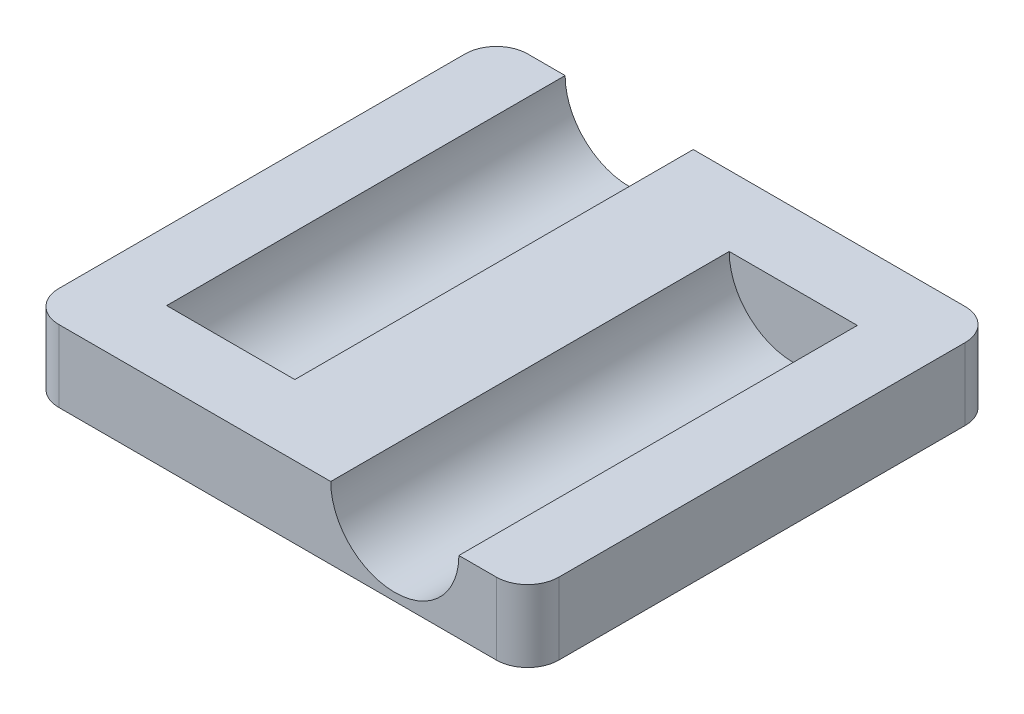
SolidWorks part; units mm, degrees
ref_plane "Front Plane" through (0, 0, 0) normal (0, 0, 1) x (1, 0, 0)
ref_plane "Top Plane" through (0, 0, 0) normal (0, 1, 0) x (1, 0, 0)
ref_plane "Right Plane" through (0, 0, 0) normal (1, 0, 0) x (0, 0, -1)
sketch "Sketch1" plane through (0, 0, 0) normal (0, 0, 1) x (1, 0, 0)
  line L1 (-12.0457, -6.5978) -> (19.9543, -6.5978)
  line L2 (-12.0457, -6.5978) -> (-12.0457, -0.0978)
  line L3 (-12.0457, -0.0978) -> (19.9543, -0.0978)
  line L4 (19.9543, -6.5978) -> (19.9543, -0.0978)
  dimension "D1" = 32
  dimension "D2" = 6.5
extrude "Boss-Extrude1" add sketch "Sketch1" along normal blind 30
fillet "Fillet1" radius 2 4 edges at (19.9543, -3.3478, 30) (-12.0457, -3.3478, 30) (-12.0457, -3.3478, 0) (19.9543, -3.3478, 0)
sketch "Sketch2" plane through (0, 0, 0) normal (0, 0, -1) x (-1, 0, 0)
  circle A0 centre (3.5457, -0.1978) radius 4.1
extrude "Cut-Extrude1" cut sketch "Sketch2" against normal blind 25.5
sketch "Sketch3" plane through (0, 0, 30) normal (0, 0, 1) x (1, 0, 0)
  circle A0 centre (11.4543, -0.1978) radius 4.1
extrude "Cut-Extrude2" cut sketch "Sketch3" against normal blind 25.5
sketch "Sketch5" plane through (0, 0, 30) normal (0, 0, 1) x (1, 0, 0)
  line L0 (19.9543, -0.0978) -> (19.9543, -6.5978) construction
  line L1 (-12.0457, -0.0978) -> (19.9543, -0.0978)
  line L2 (-12.0457, -0.0978) -> (-12.0457, -0.1978)
  line L3 (-12.0457, -0.1978) -> (19.9543, -0.1978)
  line L4 (19.9543, -0.0978) -> (19.9543, -0.1978)
  dimension "D1" = 0.1
extrude "Cut-Extrude3" cut sketch "Sketch5" against normal through all
sketch "Sketch6" plane through (0, 0, 30) normal (0, 0, 1) x (1, 0, 0)
  line L0 (-12.0457, -6.5978) -> (-12.0457, -0.1978) construction
  line L1 (19.9543, -6.5978) -> (-12.0457, -6.5978)
  line L2 (19.9543, -6.5978) -> (19.9543, -4.7978)
  line L3 (19.9543, -4.7978) -> (-12.0457, -4.7978)
  line L4 (-12.0457, -6.5978) -> (-12.0457, -4.7978)
  dimension "D1" = 1.8
extrude "Cut-Extrude4" cut sketch "Sketch6" against normal through all
